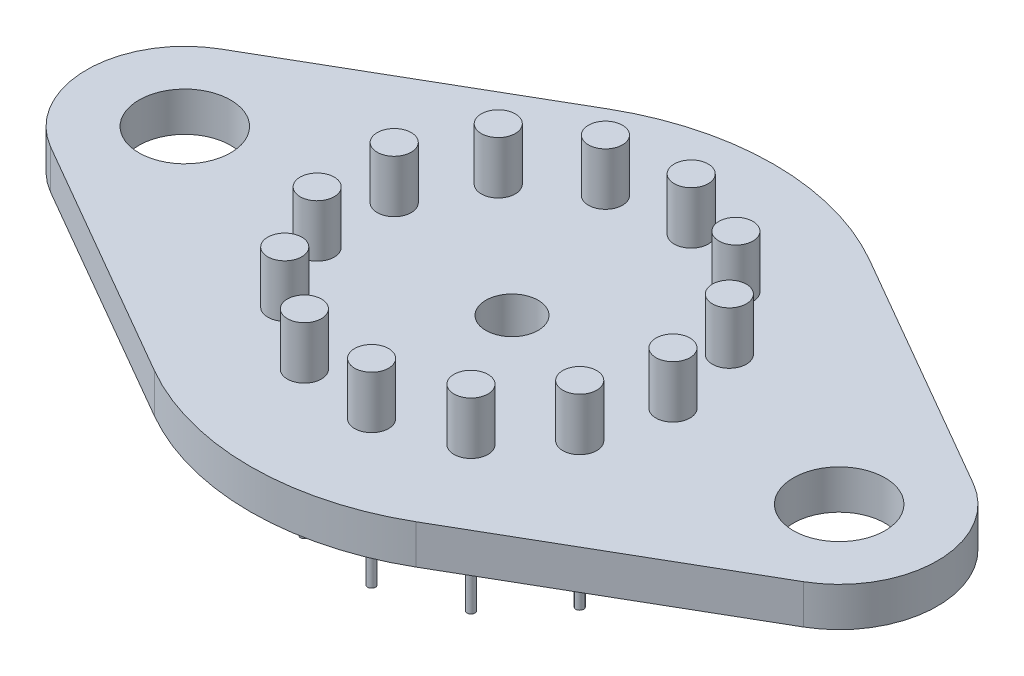
SolidWorks part; units mm, degrees
ref_plane "Plan de face" through (0, 0, 0) normal (0, 0, 1) x (1, 0, 0)
ref_plane "Plan de dessus" through (0, 0, 0) normal (0, 1, 0) x (1, 0, 0)
ref_plane "Plan de droite" through (0, 0, 0) normal (1, 0, 0) x (0, 0, -1)
sketch "Esquisse1" plane through (0, 0, 0) normal (0, 1, 0) x (1, 0, 0)
  line L0 (-12.5, 0) -> (12.5, 0) construction
  line L1 (-5, 8.6603) -> (-14.375, 3.2476)
  line L2 (-14.375, -3.2476) -> (-5, -8.6603)
  line L3 (5, 8.6603) -> (14.375, 3.2476)
  line L4 (5, -8.6603) -> (14.375, -3.2476)
  arc A0 (-5, -8.6603) -> (5, -8.6603) centre (0, 0) ccw
  arc A1 (-14.375, 3.2476) -> (-14.375, -3.2476) centre (-12.5, 0) ccw
  arc A2 (14.375, -3.2476) -> (14.375, 3.2476) centre (12.5, 0) ccw
  arc A3 (5, 8.6603) -> (-5, 8.6603) centre (0, 0) ccw
  point P9 (0, 0)
  dimension "D1" = 20
  dimension "D2" = 7.5
  dimension "D4" = 25
extrude "Boss.-Extru.1" add sketch "Esquisse1" along normal blind 1.5 contours L1 A1 L2 A0 L4 A2 L3 A3
sketch "Esquisse2" plane through (0, 1.5, 0) normal (0, 1, 0) x (1, 0, 0)
  line L0 (-12.5, 0) -> (12.5, 0) construction
  circle A0 centre (-12.5, 0) radius 1.75
  circle A1 centre (12.5, 0) radius 1.75
  point P4 (0, 0)
  dimension "D1" = 3.5
  dimension "D2" = 3.5
  dimension "D3" = 25
extrude "Enlèv. mat.-Extru.1" cut sketch "Esquisse2" against normal through all
sketch "Esquisse3" plane through (0, 1.5, 0) normal (0, 1, 0) x (1, 0, 0)
  circle A0 centre (6.15, 0) radius 0.65
  circle A1 centre (5.4456, -2.858) radius 0.65
  circle A2 centre (3.4936, -5.0614) radius 0.65
  circle A3 centre (0.7413, -6.1052) radius 0.65
  circle A4 centre (-2.1808, -5.7503) radius 0.65
  circle A5 centre (-4.6033, -4.0782) radius 0.65
  circle A6 centre (-5.9713, -1.4718) radius 0.65
  circle A7 centre (-5.9713, 1.4718) radius 0.65
  circle A8 centre (-4.6033, 4.0782) radius 0.65
  circle A9 centre (-2.1808, 5.7503) radius 0.65
  circle A10 centre (0.7413, 6.1052) radius 0.65
  circle A11 centre (3.4936, 5.0614) radius 0.65
  circle A12 centre (5.4456, 2.858) radius 0.65
  point P29 (0, 0)
  dimension "D1" = 1.3
  dimension "D2" = 6.15
  dimension "D3" = 13
extrude "Boss.-Extru.2" add sketch "Esquisse3" along normal blind 2
sketch "Esquisse4" plane through (0, 0, 0) normal (0, -1, 0) x (1, 0, 0)
  circle A0 centre (6.15, 0) radius 0.15
  circle A1 centre (5.4456, -2.858) radius 0.15
  circle A2 centre (3.4936, -5.0614) radius 0.15
  circle A3 centre (0.7413, -6.1052) radius 0.15
  circle A4 centre (-2.1808, -5.7503) radius 0.15
  circle A5 centre (-4.6033, -4.0782) radius 0.15
  circle A6 centre (-5.9713, -1.4718) radius 0.15
  circle A7 centre (-5.9713, 1.4718) radius 0.15
  circle A8 centre (-4.6033, 4.0782) radius 0.15
  circle A9 centre (-2.1808, 5.7503) radius 0.15
  circle A10 centre (0.7413, 6.1052) radius 0.15
  circle A11 centre (3.4936, 5.0614) radius 0.15
  circle A12 centre (5.4456, 2.858) radius 0.15
  dimension "D1" = 0.3
  dimension "D2" = 6.15
  dimension "D3" = 13
extrude "Boss.-Extru.3" add sketch "Esquisse4" along normal blind 4
sketch "Esquisse6" plane through (0, 1.5, 0) normal (0, 1, 0) x (1, 0, 0)
  circle A0 centre (0, 0) radius 1
  dimension "D1" = 2
extrude "Enlèv. mat.-Extru.2" cut sketch "Esquisse6" against normal through all contours A0
